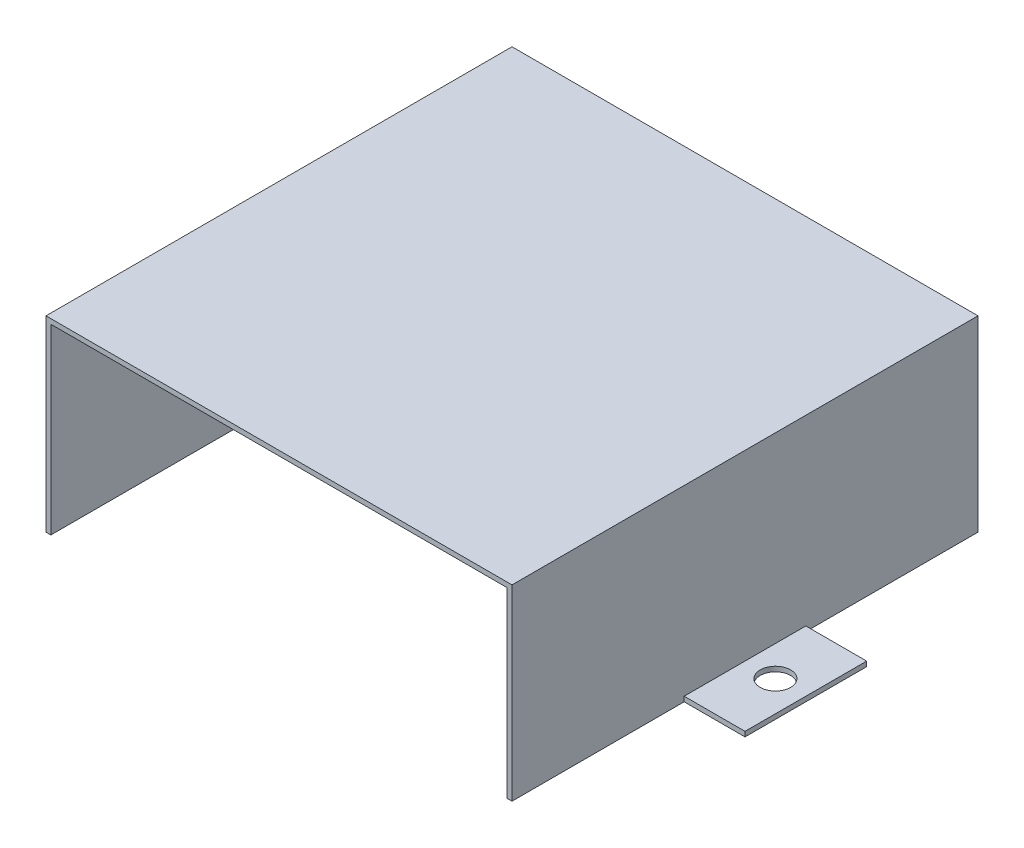
SolidWorks part; units mm, degrees
ref_plane "前视基准面" through (0, 0, 0) normal (0, 0, 1) x (1, 0, 0)
ref_plane "上视基准面" through (0, 0, 0) normal (0, 1, 0) x (1, 0, 0)
ref_plane "右视基准面" through (0, 0, 0) normal (1, 0, 0) x (0, 0, -1)
other "Configuration Table"
sketch "草图1" plane through (0, 0, 0) normal (0, 1, 0) x (1, 0, 0)
  line L1 (0, 0) -> (75, 0)
  line L2 (0, 0) -> (0, -75)
  line L3 (0, -75) -> (75, -75)
  line L4 (75, 0) -> (75, -75)
extrude "凸台-拉伸1" add sketch "草图1" along normal blind 0.8
sketch "草图2" plane through (0, 0.8, 0) normal (0, 1, 0) x (1, 0, 0)
  line L1 (0, 0) -> (75, 0)
  line L2 (0, 0) -> (0, -75)
  line L3 (0, -75) -> (75, -75)
  line L4 (75, 0) -> (75, -75)
  line L5 (-0.8, 0.8) -> (75.8, 0.8)
  line L6 (-0.8, 0.8) -> (-0.8, -75.8)
  line L7 (-0.8, -75.8) -> (75.8, -75.8)
  line L8 (75.8, 0.8) -> (75.8, -75.8)
  dimension "D1" = 0.8
  dimension "D2" = 0.8
  dimension "D3" = 0.8
  dimension "D4" = 0.8
extrude "凸台-拉伸2" add sketch "草图2" against normal blind 30.8
sketch "草图3" plane through (0, -30, 0) normal (0, -1, 0) x (1, 0, 0)
  line L0 (0, 37.5) -> (75, 37.5) construction
  line L3 (37.5, 75) -> (37.5, 0) construction
  line L4 (0, 75) -> (75, 75) construction
  line L5 (75, 0) -> (0, 0) construction
  line L6 (-0.8, 37.5) -> (-0.8, 47.5)
  line L7 (-0.8, -0.8) -> (-0.8, 75.8) construction
  line L8 (-0.8, 47.5) -> (-10.8, 47.5)
  line L9 (-10.8, 47.5) -> (-10.8, 27.5)
  line L10 (-10.8, 27.5) -> (-0.8, 27.5)
  line L11 (-0.8, 27.5) -> (-0.8, 37.5)
  line L12 (75.8, 27.5) -> (75.8, 37.5)
  line L13 (85.8, 27.5) -> (75.8, 27.5)
  line L14 (85.8, 47.5) -> (85.8, 27.5)
  line L15 (75.8, 47.5) -> (85.8, 47.5)
  line L16 (75.8, 37.5) -> (75.8, 47.5)
extrude "凸台-拉伸3" add sketch "草图3" against normal blind 0.8
hole_wizard "Ø5.0mm 暗销孔1" positions "草图6" profile "草图7" hole size "Ø5.0" standard "GB" end condition through all
sketch "草图6" plane through (0, -30, 0) normal (0, -1, 0) x (-1, 0, 0)
  line L0 (-75, -37.5) -> (0, -37.5) construction
  line L1 (-75, -75) -> (-75, 0) construction
  line L2 (0, 0) -> (0, -75) construction
  line L4 (-37.5, 0) -> (-37.5, -75) construction
  line L5 (-75, 0) -> (0, 0) construction
  line L6 (0, -75) -> (-75, -75) construction
  point P17 (-80.8, -37.5)
  point P20 (0, 0)
  point P21 (5.8, -37.5)
  dimension "D1" = 5.8
sketch "草图7" plane through (-5.8, -30, 37.5) normal (1, 0, 0) x (0, 0, -1)
  line L0 (0, 0) -> (0, 30.8)
  line L1 (0, 30.8) -> (2.5, 30.8)
  line L2 (2.5, 30.8) -> (2.5, 0)
  line L5 (2.5, 0) -> (0, 0)
  line L11 (0, -6.35) -> (0, 107.95) construction
  dimension "通孔孔直径" = 5
  dimension "通孔孔深度" = 30.8
sketch "草图8" plane through (0, 0, -0.8) normal (0, 0, -1) x (-1, 0, 0)
  line L0 (-75, -30) -> (-75, 0)
  line L1 (-75.8, -30) -> (0.8, -30) construction
  line L2 (-75, 0) -> (0, 0)
  line L3 (0, 0) -> (0, -30)
  line L4 (0, -30) -> (-75, -30)
  line L5 (-75.8, -30) -> (-75.8, 0.8) construction
  line L6 (-75.8, 0.8) -> (0.8, 0.8) construction
  line L7 (0.8, -30) -> (0.8, 0.8) construction
  dimension "D1" = 0.8
  dimension "D2" = 0.8
  dimension "D3" = 0.8
extrude "切除-拉伸1" cut sketch "草图8" against normal through all
